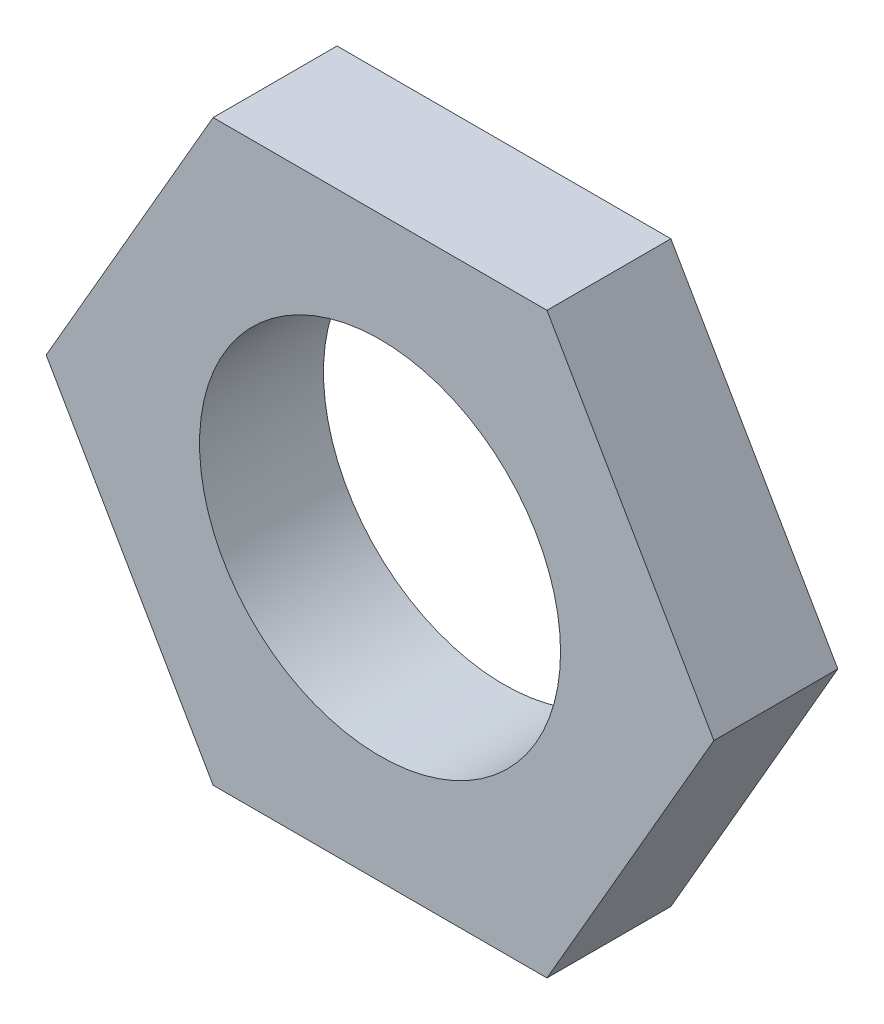
SolidWorks part; units mm, degrees
ref_plane "Front Plane" through (0, 0, 0) normal (0, 0, 1) x (1, 0, 0)
ref_plane "Top Plane" through (0, 0, 0) normal (0, 1, 0) x (1, 0, 0)
ref_plane "Right Plane" through (0, 0, 0) normal (1, 0, 0) x (0, 0, -1)
sketch "Sketch1" plane through (0, 0, 0) normal (0, 0, 1) x (1, 0, 0)
  line L1 (4.0415, 0) -> (2.0207, 3.5)
  line L2 (2.0207, 3.5) -> (-2.0207, 3.5)
  line L3 (-2.0207, 3.5) -> (-4.0415, 0)
  line L4 (-4.0415, 0) -> (-2.0207, -3.5)
  line L5 (-2.0207, -3.5) -> (2.0207, -3.5)
  line L6 (2.0207, -3.5) -> (4.0415, 0)
  circle A0 centre (0, 0) radius 2.185
  circle A1 centre (0, 0) radius 3.5 construction
  dimension "D1" = 4.37
  dimension "D2" = 7
extrude "Boss-Extrude1" add sketch "Sketch1" along normal blind 1.5
